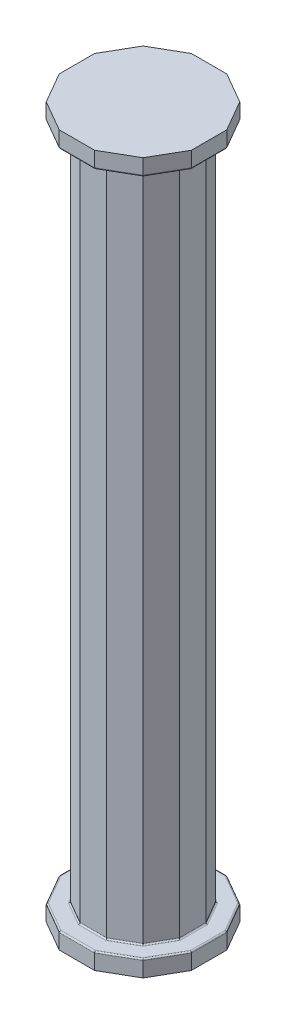
SolidWorks part; units mm, degrees
material "AISI 1020"
ref_plane "Front Plane" through (0, 0, 0) normal (0, 0, 1) x (1, 0, 0)
ref_plane "Top Plane" through (0, 0, 0) normal (0, 1, 0) x (1, 0, 0)
ref_plane "Right Plane" through (0, 0, 0) normal (1, 0, 0) x (0, 0, -1)
sketch "Sketch1" plane through (0, 0, 0) normal (0, 1, 0) x (1, 0, 0)
  line L0 (-55, 0) -> (55, 0) construction
  line L1 (-122.5064, 457.2) -> (-334.6936, 334.6936)
  line L2 (-334.6936, 334.6936) -> (-457.2, 122.5064)
  line L3 (-457.2, 122.5064) -> (-457.2, -122.5064)
  line L4 (-457.2, -122.5064) -> (-334.6936, -334.6936)
  line L5 (-334.6936, -334.6936) -> (-122.5064, -457.2)
  line L6 (-122.5064, -457.2) -> (122.5064, -457.2)
  line L7 (122.5064, -457.2) -> (334.6936, -334.6936)
  line L8 (334.6936, -334.6936) -> (457.2, -122.5064)
  line L9 (457.2, -122.5064) -> (457.2, 122.5064)
  line L10 (457.2, 122.5064) -> (334.6936, 334.6936)
  line L11 (334.6936, 334.6936) -> (122.5064, 457.2)
  line L12 (122.5064, 457.2) -> (-122.5064, 457.2)
  circle A0 centre (0, 0) radius 457.2 construction
  dimension "D1" = 914.4
extrude "Support Base" add sketch "Sketch1" along normal blind 6248.4
sketch "Sketch2" plane through (0, 0, 0) normal (0, -1, 0) x (1, 0, 0)
  line L24 (-163.3418, -609.6) -> (163.3418, -609.6)
  line L25 (163.3418, -609.6) -> (446.2582, -446.2582)
  line L26 (446.2582, -446.2582) -> (609.6, -163.3418)
  line L27 (609.6, -163.3418) -> (609.6, 163.3418)
  line L28 (609.6, 163.3418) -> (446.2582, 446.2582)
  line L29 (446.2582, 446.2582) -> (163.3418, 609.6)
  line L30 (163.3418, 609.6) -> (-163.3418, 609.6)
  line L31 (-163.3418, 609.6) -> (-446.2582, 446.2582)
  line L32 (-446.2582, 446.2582) -> (-609.6, 163.3418)
  line L33 (-609.6, 163.3418) -> (-609.6, -163.3418)
  line L34 (-609.6, -163.3418) -> (-446.2582, -446.2582)
  line L35 (-446.2582, -446.2582) -> (-163.3418, -609.6)
  line L36 (-163.3418, -609.6) -> (163.3418, -609.6)
  line L37 (163.3418, -609.6) -> (446.2582, -446.2582)
  line L38 (446.2582, -446.2582) -> (609.6, -163.3418)
  line L39 (609.6, -163.3418) -> (609.6, 163.3418)
  line L40 (609.6, 163.3418) -> (446.2582, 446.2582)
  line L41 (446.2582, 446.2582) -> (163.3418, 609.6)
  line L42 (163.3418, 609.6) -> (-163.3418, 609.6)
  line L43 (-163.3418, 609.6) -> (-446.2582, 446.2582)
  line L44 (-446.2582, 446.2582) -> (-609.6, 163.3418)
  line L45 (-609.6, 163.3418) -> (-609.6, -163.3418)
  line L46 (-609.6, -163.3418) -> (-446.2582, -446.2582)
  line L47 (-446.2582, -446.2582) -> (-163.3418, -609.6)
  dimension "D1" = 152.4
extrude "Bottom Extrude" add sketch "Sketch2" along normal blind 152.4
ref_plane "Midplane" through (0, 3124.2, 0) normal (0, 1, 0) x (1, 0, 0)
mirror "Top Extrude" about plane through (0, 3124.2, 0) normal (0, 1, 0) of "Bottom Extrude"
fillet "Face Fillet" radius 12.7 48 edges at (395.9468, 6248.4, -228.6) (457.2, 6248.4, 0) (395.9468, 6248.4, 228.6) (228.6, 6248.4, 395.9468) (0, 6248.4, 457.2) (-228.6, 6248.4, 395.9468) (-395.9468, 6248.4, 228.6) (-457.2, 6248.4, 0) (-395.9468, 6248.4, -228.6) (-228.6, 6248.4, -395.9468) (0, 6248.4, -457.2) (228.6, 6248.4, -395.9468) (-527.9291, 6248.4, -304.8) (-609.6, 6248.4, 0) (-527.9291, 6248.4, 304.8) (-304.8, 6248.4, 527.9291) (0, 6248.4, 609.6) (304.8, 6248.4, 527.9291) (527.9291, 6248.4, 304.8) (609.6, 6248.4, 0) (527.9291, 6248.4, -304.8) (304.8, 6248.4, -527.9291) (0, 6248.4, -609.6) (-304.8, 6248.4, -527.9291) (0, 0, -609.6) (304.8, 0, -527.9291) (527.9291, 0, -304.8) (609.6, 0, 0) (527.9291, 0, 304.8) (304.8, 0, 527.9291) (0, 0, 609.6) (-304.8, 0, 527.9291) (-527.9291, 0, 304.8) (-609.6, 0, 0) (-527.9291, 0, -304.8) (-304.8, 0, -527.9291) (-228.6, 0, -395.9468) (-395.9468, 0, -228.6) (-457.2, 0, 0) (-395.9468, 0, 228.6) (-228.6, 0, 395.9468) (0, 0, 457.2) (228.6, 0, 395.9468) (395.9468, 0, 228.6) (457.2, 0, 0) (395.9468, 0, -228.6) (228.6, 0, -395.9468) (0, 0, -457.2)
